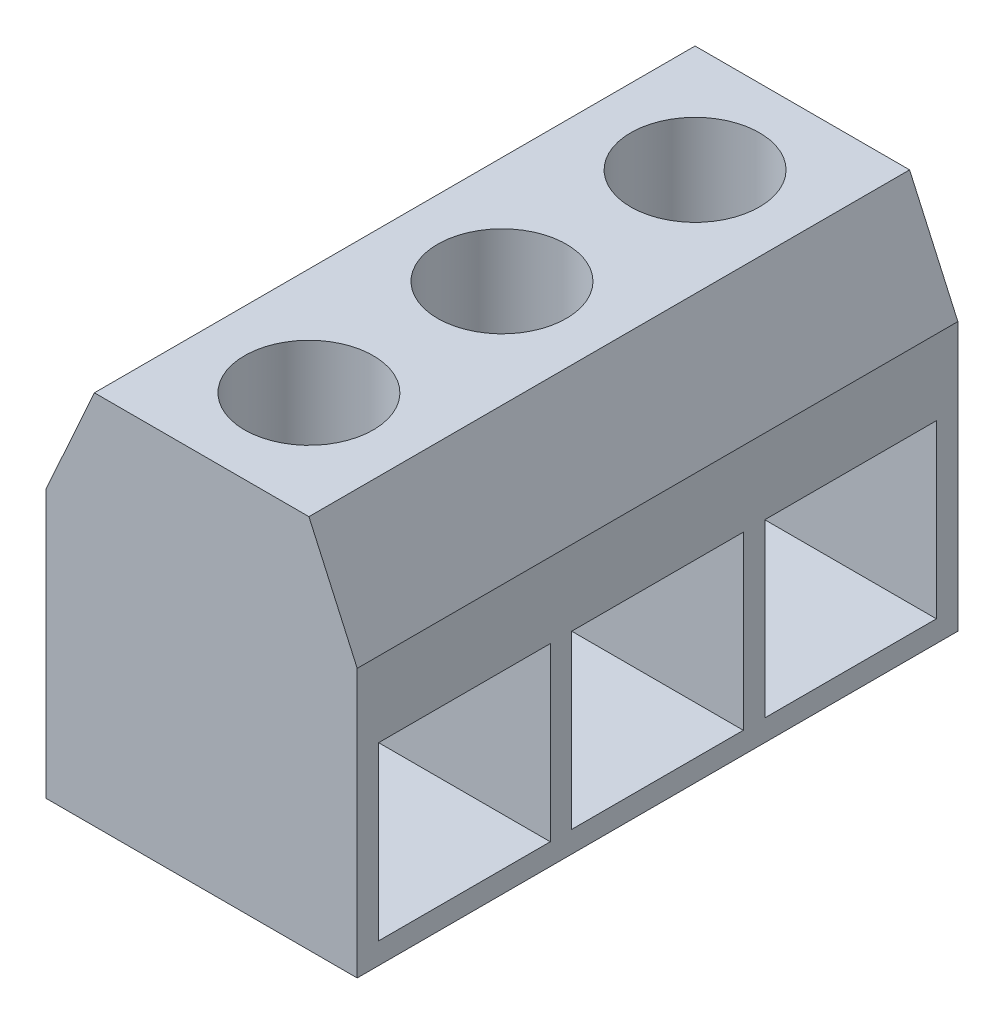
SolidWorks part; units mm, degrees
material "自定义塑料"
ref_plane "前视基准面" through (0, 0, 0) normal (0, 0, 1) x (1, 0, 0)
ref_plane "上视基准面" through (0, 0, 0) normal (0, 1, 0) x (1, 0, 0)
ref_plane "右视基准面" through (0, 0, 0) normal (1, 0, 0) x (0, 0, -1)
sketch "草图1" plane through (0, 0, 0) normal (0, 0, 1) x (1, 0, 0)
  line L0 (3.683, 8.89) -> (1.143, 8.89) construction
  line L1 (0, 0) -> (7.366, 0)
  line L2 (0, 0) -> (0, 6.35)
  line L3 (1.143, 8.89) -> (6.223, 8.89)
  line L4 (7.366, 0) -> (7.366, 6.35)
  line L5 (0, 0) -> (0, 6.35) construction
  line L6 (1.143, 8.89) -> (0, 6.35)
  line L7 (3.683, 8.89) -> (3.683, 0) construction
  line L8 (6.223, 8.89) -> (7.366, 6.35)
extrude "凸台-拉伸1" add sketch "草图1" along normal blind 14.224
ref_plane "基准面1" through (0, 8.89, 0) normal (0, 1, 0) x (1, 0, 0)
sketch "草图2" plane through (0, 8.89, 0) normal (0, 1, 0) x (1, 0, 0)
  line L0 (3.683, 0) -> (3.683, -14.224) construction
  line L1 (6.223, 0) -> (1.143, 0) construction
  line L2 (6.223, -14.224) -> (1.143, -14.224) construction
  line L3 (3.683, 0) -> (3.683, -2.54) construction
  line L4 (6.223, -7.112) -> (1.143, -7.112) construction
  line L5 (6.223, -14.224) -> (6.223, 0) construction
  line L6 (1.143, -14.224) -> (1.143, 0) construction
  circle A0 centre (3.683, -2.54) radius 1.524
  circle A1 centre (3.683, -11.684) radius 1.524
  circle A2 centre (3.683, -7.112) radius 1.524
extrude "切除-拉伸1" cut sketch "草图2" against normal blind 8.382
ref_plane "基准面2" through (7.366, 0, 0) normal (1, 0, 0) x (0, 0, -1)
sketch "草图3" plane through (7.366, 0, 0) normal (1, 0, 0) x (0, 0, -1)
  line L0 (-14.224, 0) -> (-14.224, 0.508) construction
  line L1 (-14.224, 0) -> (-14.224, 6.35) construction
  line L2 (-14.224, 0.508) -> (-13.716, 0.508) construction
  line L3 (-7.112, 0) -> (-7.112, 6.35) construction
  line L4 (-13.716, 0.508) -> (-9.652, 0.508)
  line L5 (-13.716, 0.508) -> (-13.716, 4.572)
  line L6 (-13.716, 4.572) -> (-9.652, 4.572)
  line L7 (-9.652, 0.508) -> (-9.652, 4.572)
  line L8 (-14.224, 0) -> (0, 0) construction
  line L9 (-14.224, 6.35) -> (0, 6.35) construction
  line L10 (-7.112, 0.508) -> (-9.144, 0.508)
  line L11 (-9.144, 0.508) -> (-9.144, 4.572)
  line L12 (-9.144, 4.572) -> (-5.08, 4.572)
  line L13 (-5.08, 4.572) -> (-5.08, 0.508)
  line L14 (-5.08, 0.508) -> (-7.112, 0.508)
  line L15 (0, 0.508) -> (-0.508, 0.508) construction
  line L16 (0, 0) -> (0, 0.508) construction
  line L17 (-4.572, 0.508) -> (-4.572, 4.572)
  line L18 (-0.508, 4.572) -> (-4.572, 4.572)
  line L19 (-0.508, 0.508) -> (-0.508, 4.572)
  line L20 (-0.508, 0.508) -> (-4.572, 0.508)
extrude "切除-拉伸2" cut sketch "草图3" against normal blind 5.334
sketch "草图4" plane through (0, 0, 0) normal (0, 0, 1) x (1, 0, 0)
  line L0 (0, 0) -> (1.016, 0) construction
  line L1 (0, 0) -> (7.366, 0) construction
  line L2 (1.016, 0) -> (1.016, 6.35)
  line L3 (1.016, 6.35) -> (1.778, 6.35)
  line L4 (1.778, 6.35) -> (1.778, 0)
  line L5 (1.778, 0) -> (1.016, 0)
extrude "切除-拉伸3" cut sketch "草图4" along normal blind 1.27
